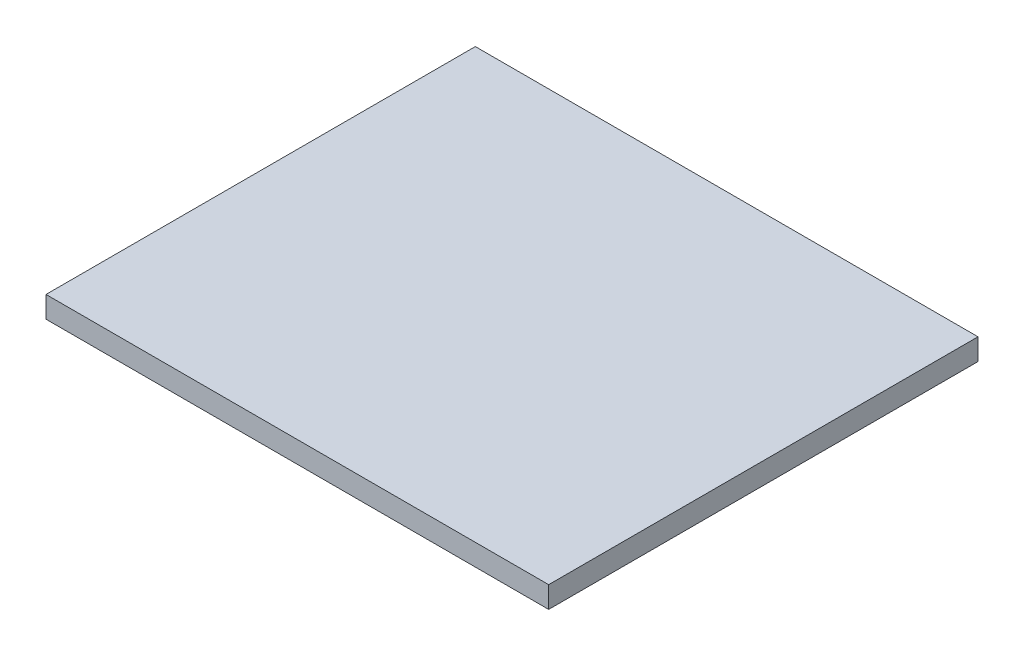
SolidWorks part; units mm, degrees
ref_plane "Front Plane" through (0, 0, 0) normal (0, 0, 1) x (1, 0, 0)
ref_plane "Top Plane" through (0, 0, 0) normal (0, 1, 0) x (1, 0, 0)
ref_plane "Right Plane" through (0, 0, 0) normal (1, 0, 0) x (0, 0, -1)
sketch "Sketch1" plane through (0, 0, 0) normal (0, 1, 0) x (1, 0, 0)
  line L1 (-140.5, -120) -> (140.5, -120)
  line L2 (-140.5, -120) -> (-140.5, 120)
  line L3 (-140.5, 120) -> (140.5, 120)
  line L4 (140.5, -120) -> (140.5, 120)
  line L5 (-140.5, -120) -> (140.5, 120) construction
  line L6 (-140.5, 120) -> (140.5, -120) construction
  point P0 (0, 0)
  dimension "D1" = 281
  dimension "D2" = 240
extrude "Boss-Extrude1" add sketch "Sketch1" along normal blind 12
